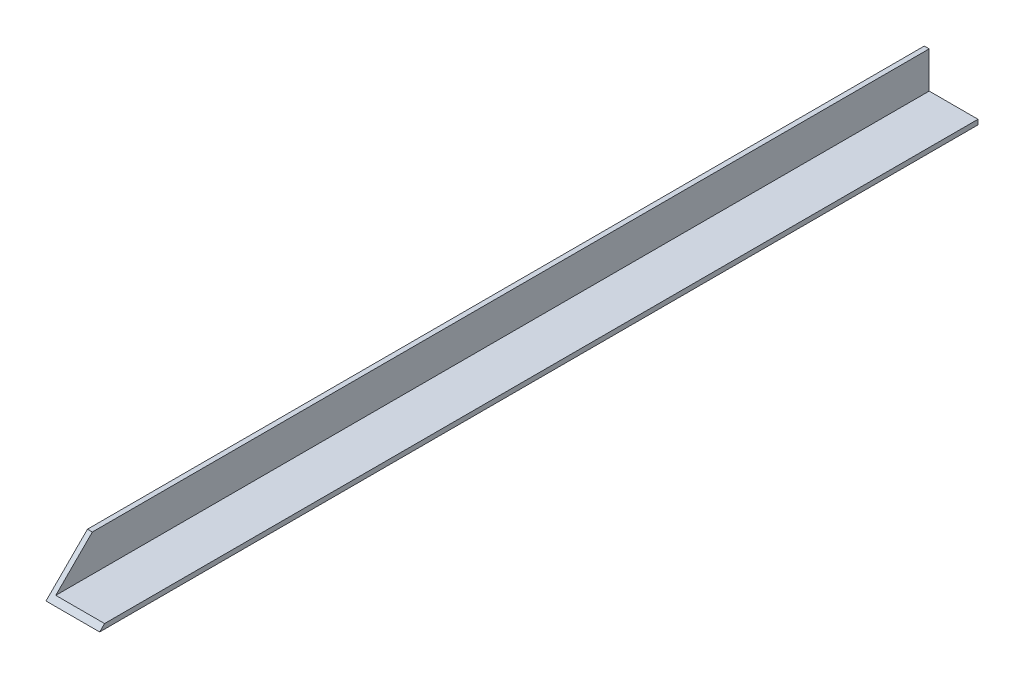
SolidWorks part; units mm, degrees
ref_plane "Front Plane" through (0, 0, 0) normal (0, 0, 1) x (1, 0, 0)
ref_plane "Top Plane" through (0, 0, 0) normal (0, 1, 0) x (1, 0, 0)
ref_plane "Right Plane" through (0, 0, 0) normal (1, 0, 0) x (0, 0, -1)
sketch "Sketch1" plane through (0, 0, 0) normal (0, 0, 1) x (1, 0, 0)
  line L0 (0, 0) -> (0, 17)
  line L1 (0, 17) -> (2, 17)
  line L2 (2, 17) -> (2, 2)
  line L3 (2, 2) -> (22, 2)
  line L4 (22, 2) -> (22, 0)
  line L5 (22, 0) -> (0, 0)
  dimension "D1" = 17
  dimension "D2" = 22
  dimension "D3" = 2
  dimension "D4" = 2
extrude "Boss-Extrude1" add sketch "Sketch1" against normal blind 360
sketch "Sketch2" plane through (2, 0, 0) normal (1, 0, 0) x (0, 0, -1)
  line L0 (0, 0) -> (0, 17)
  line L1 (0, 17) -> (17, 17)
  line L2 (360, 17) -> (0, 17) construction
  line L3 (17, 17) -> (0, 0)
  dimension "D1" = 45
extrude "Cut-Extrude1" cut sketch "Sketch2" along normal through all both and the other way through all
